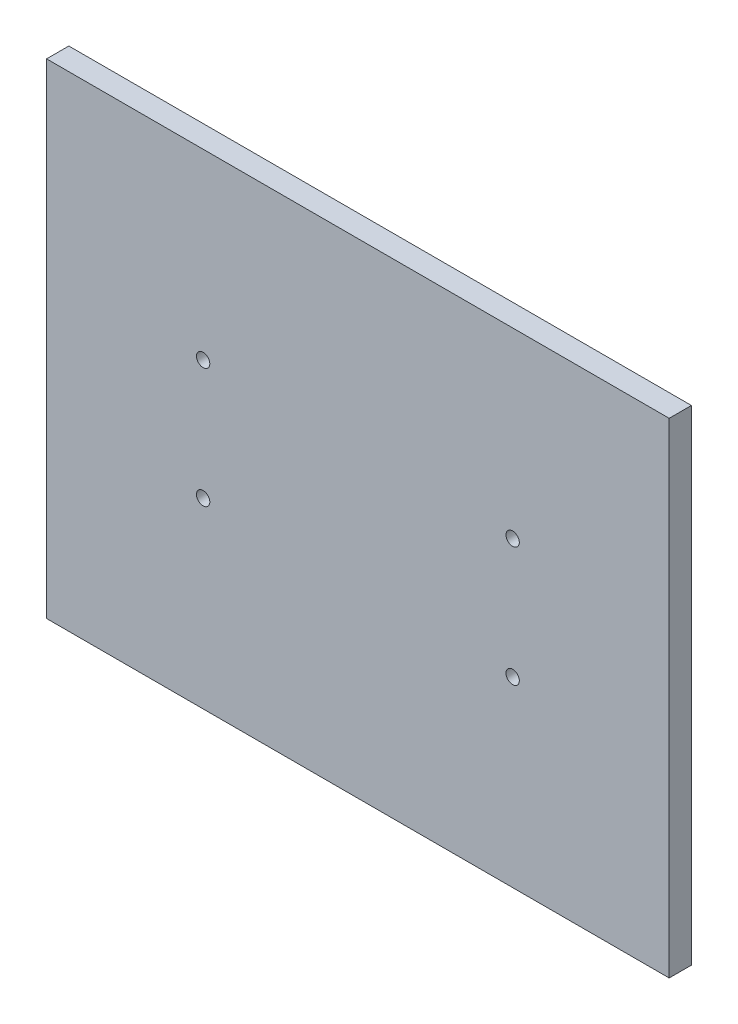
SolidWorks part; units mm, degrees
ref_plane "Front Plane" through (0, 0, 0) normal (0, 0, 1) x (1, 0, 0)
ref_plane "Top Plane" through (0, 0, 0) normal (0, 1, 0) x (1, 0, 0)
ref_plane "Right Plane" through (0, 0, 0) normal (1, 0, 0) x (0, 0, -1)
sketch "Sketch1" plane through (0, 0, 0) normal (0, 0, 1) x (1, 0, 0)
  line L1 (-70, -54.5) -> (70, -54.5)
  line L2 (-70, -54.5) -> (-70, 54.5)
  line L3 (-70, 54.5) -> (70, 54.5)
  line L4 (70, -54.5) -> (70, 54.5)
  line L5 (-70, -54.5) -> (70, 54.5) construction
  line L6 (-70, 54.5) -> (70, -54.5) construction
  point P0 (0, 0)
  dimension "D1" = 140
  dimension "D2" = 109
extrude "Boss-Extrude1" add sketch "Sketch1" along normal blind 5
sketch "Sketch2" plane through (0, 0, 5) normal (0, 0, 1) x (1, 0, 0)
  circle A0 centre (-34.8, 13.46) radius 1.5
  circle A1 centre (34.8, 13.46) radius 1.5
  circle A2 centre (34.8, -13.46) radius 1.5
  circle A3 centre (-34.8, -13.46) radius 1.5
  dimension "D1" = 3
  dimension "D5" = 2
  dimension "D2" = 13.46
  dimension "D4" = 34.8
  dimension "D3" = 2
extrude "Cut-Extrude1" cut sketch "Sketch2" against normal blind 5
